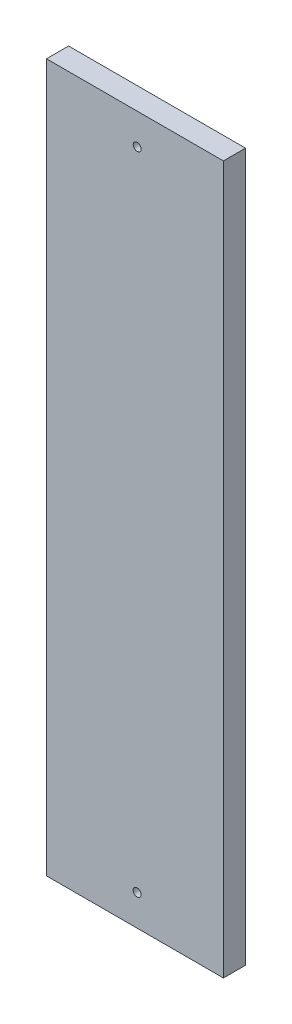
SolidWorks part; units mm, degrees
ref_plane "Front Plane" through (0, 0, 0) normal (0, 0, 1) x (1, 0, 0)
ref_plane "Top Plane" through (0, 0, 0) normal (0, 1, 0) x (1, 0, 0)
ref_plane "Right Plane" through (0, 0, 0) normal (1, 0, 0) x (0, 0, -1)
sketch "Sketch1" plane through (0, 0, 0) normal (0, 1, 0) x (1, 0, 0)
  line L1 (-25.4, -3.175) -> (25.4, -3.175)
  line L2 (-25.4, -3.175) -> (-25.4, 3.175)
  line L3 (-25.4, 3.175) -> (25.4, 3.175)
  line L4 (25.4, -3.175) -> (25.4, 3.175)
  line L5 (-25.4, -3.175) -> (25.4, 3.175) construction
  line L6 (-25.4, 3.175) -> (25.4, -3.175) construction
  point P0 (0, 0)
  dimension "D1" = 6.35
  dimension "D2" = 50.8
extrude "Boss-Extrude1" add sketch "Sketch1" along normal blind 203.2
sketch "Sketch3" plane through (0, 0, 3.175) normal (0, 0, 1) x (1, 0, 0)
  line L0 (25.4, 101.6) -> (-25.4, 101.6) construction
  line L1 (25.4, 203.2) -> (25.4, 0) construction
  line L2 (-25.4, 203.2) -> (-25.4, 0) construction
  circle A0 centre (0.635, 194.31) radius 1.1303
  circle A1 centre (0.635, 8.89) radius 1.1303
extrude "Cut-Extrude1" cut sketch "Sketch3" against normal through all
